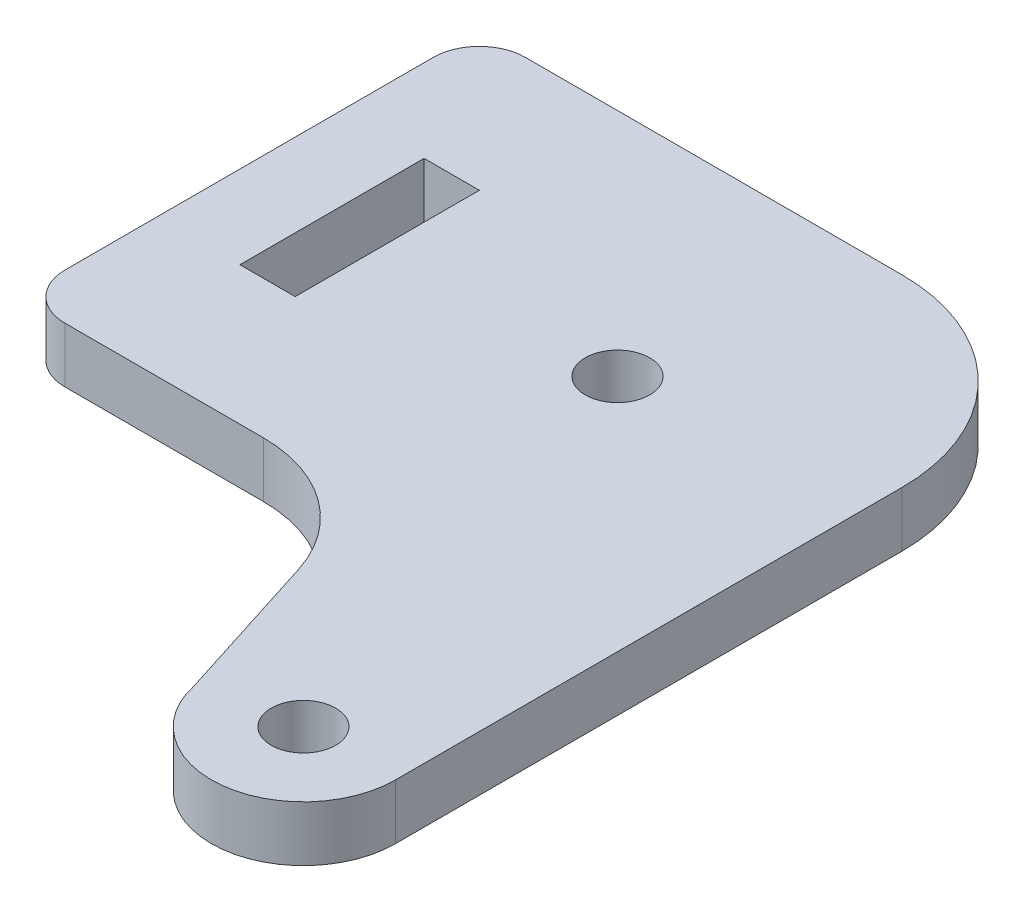
SolidWorks part; units mm, degrees
ref_plane "Front Plane" through (0, 0, 0) normal (0, 0, 1) x (1, 0, 0)
ref_plane "Top Plane" through (0, 0, 0) normal (0, 1, 0) x (1, 0, 0)
ref_plane "Right Plane" through (0, 0, 0) normal (1, 0, 0) x (0, 0, -1)
sketch "Sketch1" plane through (0, 0, 0) normal (0, 1, 0) x (1, 0, 0)
  line L0 (-45, 0) -> (45, 0) construction
  line L1 (0, 0) -> (0, -141.54) construction
  line L2 (0, -141.54) -> (-45, 0) construction
  line L3 (45, 0) -> (0, -141.54) construction
  line L4 (37.0517, -25) -> (-37.0517, -25) construction
  line L5 (-37.0517, -25) -> (-45, 0) construction
  line L8 (-45, 0) -> (45, 0) construction
  line L9 (-45, 5) -> (45, 5) construction
  line L10 (-45, -5) -> (45, -5) construction
  line L15 (-32.0517, -25) -> (-32.0517, 2.5)
  line L16 (-51.732, -12.5) -> (-62.5, -12.5)
  line L17 (-41.9436, -26.0343) -> (-44.5845, -17.7276)
  line L19 (-65, -10) -> (-65, 10)
  line L20 (-62.5, 12.5) -> (-42.0517, 12.5)
  line L22 (-60.5, -5) -> (-57.5, -5)
  line L23 (-60.5, -5) -> (-60.5, 5)
  line L24 (-60.5, 5) -> (-57.5, 5)
  line L25 (-57.5, -5) -> (-57.5, 5)
  line L26 (-60.5, -5) -> (-57.5, 5) construction
  line L27 (-60.5, 5) -> (-57.5, -5) construction
  arc A2 (-45, 5) -> (-45, -5) centre (-45, 0) ccw construction
  arc A3 (45, -5) -> (45, 5) centre (45, 0) ccw construction
  circle A7 centre (45, 0) radius 1.75 construction
  circle A8 centre (-45, 0) radius 1.75 construction
  arc A9 (-41.9436, -26.0343) -> (-32.0517, -25) centre (-37.0517, -25) ccw
  arc A11 (-62.5, -12.5) -> (-65, -10) centre (-62.5, -10) cw
  arc A12 (-62.5, 12.5) -> (-65, 10) centre (-62.5, 10) ccw
  arc A13 (-32.0517, 2.5) -> (-42.0517, 12.5) centre (-42.0517, 2.5) ccw
  circle A16 centre (-45, 0) radius 1.75
  arc A17 (-44.5845, -17.7276) -> (-51.732, -12.5) centre (-51.732, -20) ccw
  circle A18 centre (-37.0517, -25) radius 1.75
  point P8 (0, -25)
  point P13 (0, 0)
  point P21 (-59, 0)
  point P28 (-65, -12.5)
  point P33 (-65, 12.5)
  point P36 (-32.0517, 12.5)
  dimension "D4" = 12.5
  dimension "D5" = 5
  dimension "D6" = 20
  dimension "D7" = 3.5
  dimension "D8" = 3.5
  dimension "D9" = 5
  dimension "D11" = 2.5
  dimension "D12" = 10
  dimension "D15" = 4.5
  dimension "D16" = 3.5
  dimension "D17" = 7.5
  dimension "D1" = 90
  dimension "D2" = 141.54
  dimension "D3" = 25
  dimension "D10" = 25
  dimension "D13" = 3
  dimension "D14" = 10
extrude "Boss-Extrude1" add sketch "Sketch1" along normal blind 3
